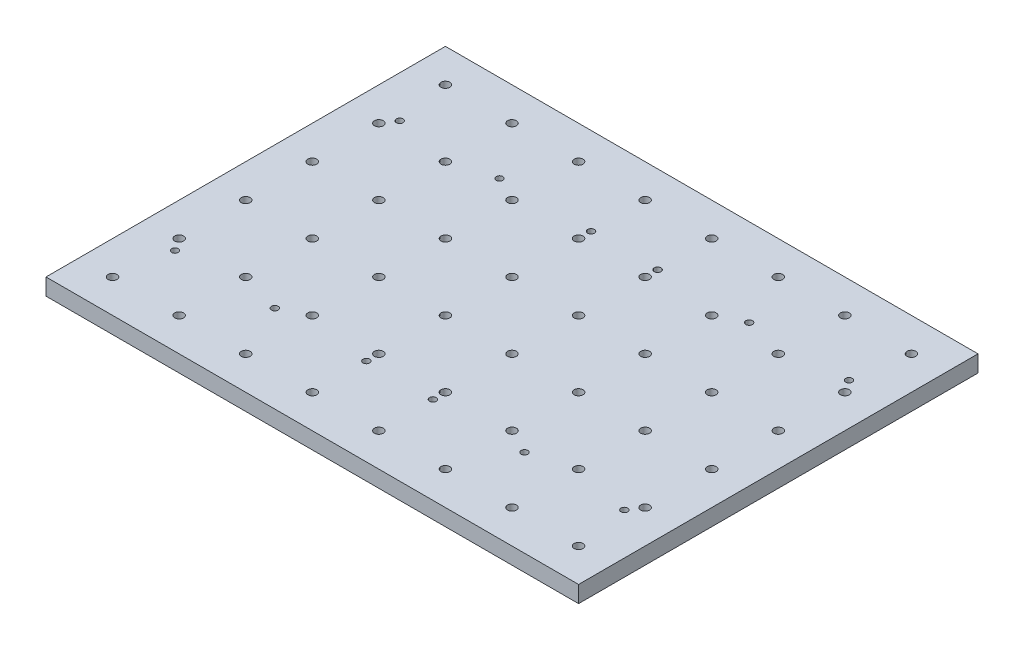
SolidWorks part; units mm, degrees
material "6061-T6 (SS)"
ref_plane "Front Plane" through (0, 0, 0) normal (0, 0, 1) x (1, 0, 0)
ref_plane "Top Plane" through (0, 0, 0) normal (0, 1, 0) x (1, 0, 0)
ref_plane "Right Plane" through (0, 0, 0) normal (1, 0, 0) x (0, 0, -1)
sketch "Sketch2" plane through (0, 0, 0) normal (0, 1, 0) x (1, 0, 0)
  line L1 (-203.2, -152.4) -> (203.2, -152.4)
  line L2 (-203.2, -152.4) -> (-203.2, 152.4)
  line L3 (-203.2, 152.4) -> (203.2, 152.4)
  line L4 (203.2, -152.4) -> (203.2, 152.4)
  line L5 (-203.2, -152.4) -> (203.2, 152.4) construction
  line L6 (-203.2, 152.4) -> (203.2, -152.4) construction
  point P0 (0, 0)
  dimension "D1" = 406.4
  dimension "D2" = 304.8
extrude "Boss-Extrude1" add sketch "Sketch2" along normal blind 12.7
hole_wizard "1/4 Clearance Hole1" positions "Sketch3" profile "Sketch4" hole size "1/4" standard "ANSI Inch" end condition through all
sketch "Sketch3" plane through (0, 12.7, 0) normal (0, 1, 0) x (1, 0, 0)
  line L0 (-203.2, -152.4) -> (203.2, -152.4) construction
  line L1 (-203.2, 152.4) -> (-203.2, -152.4) construction
  point P0 (-177.8, -127)
  dimension "D1" = 25.4
  dimension "D2" = 25.4
sketch "Sketch4" plane through (-177.8, 12.7, 127) normal (1, 0, 0) x (0, 0, 1)
  line L0 (0, 0) -> (0, 12.7)
  line L1 (0, 12.7) -> (3.3782, 12.7)
  line L2 (3.3782, 12.7) -> (3.3782, 0)
  line L5 (3.3782, 0) -> (0, 0)
  line L11 (0, -6.35) -> (0, 107.95) construction
  dimension "Thru Hole Dia." = 6.7564
  dimension "Thru Hole Depth" = 12.7
pattern_linear "LPattern1" count 6 spacing 50.8 along (0, 0, -1) count 8 spacing 50.8 along (1, 0, 0) of "1/4 Clearance Hole1"
hole_wizard "1/4-20 Tapped Hole1" positions "Sketch5" profile "Sketch6" tap size "1/4-20" standard "ANSI Inch" end condition through all
sketch "Sketch5" plane through (0, 12.7, 0) normal (0, 1, 0) x (1, 0, 0)
  point P0 (-25.4, -85.725)
  point P2 (-95.25, -85.725)
  point P6 (-171.45, -85.725)
  dimension "D1" = 69.85
  dimension "D2" = 85.725
  dimension "D3" = 25.4
  dimension "D4" = 76.2
  dimension "D5" = 85.725
sketch "Sketch6" plane through (-25.4, 12.7, 85.725) normal (1, 0, 0) x (0, 0, 1)
  line L0 (0, 0) -> (0, 12.7)
  line L1 (0, 12.7) -> (2.5527, 12.7)
  line L2 (2.5527, 12.7) -> (2.5527, 0)
  line L5 (2.5527, 0) -> (0, 0)
  line L11 (0, -6.35) -> (0, 107.95) construction
  dimension "Thru Tap Drill Dia." = 5.1054
  dimension "Thru Tap Drill Depth" = 12.7
cosmetic thread "Hole Thread1" parameters "D2"=6.35
cosmetic thread "Hole Thread2" parameters "D2"=6.35
cosmetic thread "Hole Thread9" parameters "D2"=6.35
mirror "Mirror1" about plane through (0, 0, 0) normal (0, 0, 1) of "1/4-20 Tapped Hole1"
cosmetic thread "Hole Thread3" parameters "D2"=6.35
cosmetic thread "Hole Thread4" parameters "D2"=6.35
cosmetic thread "Hole Thread10" parameters "D2"=6.35
mirror "Mirror2" about plane through (0, 0, 0) normal (1, 0, 0) of "Mirror1", "1/4-20 Tapped Hole1"
cosmetic thread "Hole Thread5" parameters "D2"=6.35
cosmetic thread "Hole Thread6" parameters "D2"=6.35
cosmetic thread "Hole Thread7" parameters "D2"=6.35
cosmetic thread "Hole Thread8" parameters "D2"=6.35
cosmetic thread "Hole Thread11" parameters "D2"=6.35
cosmetic thread "Hole Thread12" parameters "D2"=6.35
